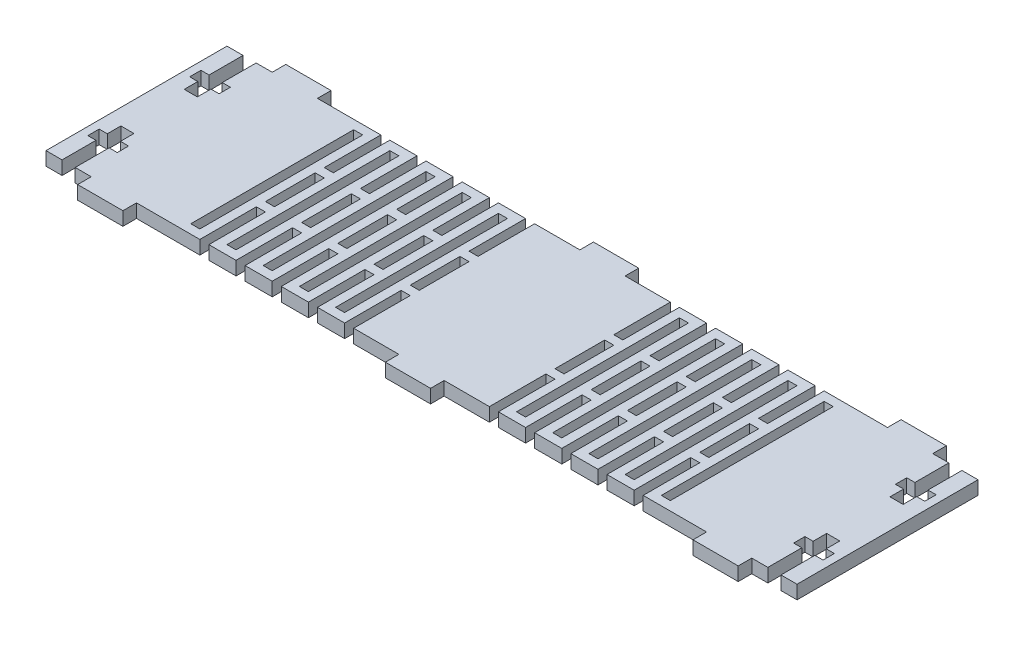
SolidWorks part; units mm, degrees
ref_plane "Front Plane" through (0, 0, 0) normal (0, 0, 1) x (1, 0, 0)
ref_plane "Top Plane" through (0, 0, 0) normal (0, 1, 0) x (1, 0, 0)
ref_plane "Right Plane" through (0, 0, 0) normal (1, 0, 0) x (0, 0, -1)
sketch "Sketch1" plane through (0, 0, 0) normal (0, 1, 0) x (1, 0, 0)
  line L0 (-53, 38) -> (-53, 2)
  line L1 (-83, 40) -> (-79.45, 40)
  line L2 (-83, 40) -> (-83, 0)
  line L3 (-83, 0) -> (-79.45, 0)
  line L5 (-15, 40) -> (-15, 27.5)
  line L8 (-51, 38) -> (-51, 2)
  line L9 (-49, 40) -> (-49, 27.5)
  line L10 (-47, 40) -> (-47, 27.5)
  line L11 (-45, 38) -> (-45, 2)
  line L12 (-43, 38) -> (-43, 2)
  line L13 (-41, 40) -> (-41, 27.5)
  line L14 (-39, 40) -> (-39, 27.5)
  line L15 (-37, 38) -> (-37, 2)
  line L16 (-35, 38) -> (-35, 2)
  line L17 (-33, 40) -> (-33, 27.5)
  line L18 (-31, 40) -> (-31, 27.5)
  line L19 (-29, 38) -> (-29, 2)
  line L20 (-27, 38) -> (-27, 2)
  line L21 (-25, 40) -> (-25, 27.5)
  line L22 (-23, 40) -> (-23, 27.5)
  line L23 (-21, 38) -> (-21, 2)
  line L24 (-19, 38) -> (-19, 2)
  line L25 (-17, 40) -> (-17, 27.5)
  line L44 (-53, 38) -> (-51, 38)
  line L45 (-53, 2) -> (-51, 2)
  line L46 (-49, 27.5) -> (-47, 27.5)
  line L47 (-49, 25.5) -> (-47, 25.5)
  line L48 (-49, 14.5) -> (-47, 14.5)
  line L49 (-49, 12.5) -> (-47, 12.5)
  line L50 (-45, 38) -> (-43, 38)
  line L51 (-47, 0) -> (-41, 0)
  line L52 (-49, 25.5) -> (-49, 14.5)
  line L53 (-49, 12.5) -> (-49, 0)
  line L54 (-45, 2) -> (-43, 2)
  line L55 (-39, 0) -> (-33, 0)
  line L56 (-41, 12.5) -> (-39, 12.5)
  line L57 (-41, 14.5) -> (-39, 14.5)
  line L58 (-41, 25.5) -> (-39, 25.5)
  line L59 (-41, 27.5) -> (-39, 27.5)
  line L60 (-47, 12.5) -> (-47, 0)
  line L61 (-47, 25.5) -> (-47, 14.5)
  line L62 (-47, 40) -> (-41, 40)
  line L63 (-33, 12.5) -> (-33, 0)
  line L64 (-41, 25.5) -> (-41, 14.5)
  line L65 (-39, 25.5) -> (-39, 14.5)
  line L66 (-41, 12.5) -> (-41, 0)
  line L67 (-39, 12.5) -> (-39, 0)
  line L68 (-39, 40) -> (-33, 40)
  line L69 (-31, 12.5) -> (-31, 0)
  line L70 (-33, 25.5) -> (-33, 14.5)
  line L71 (-31, 25.5) -> (-31, 14.5)
  line L72 (-37, 38) -> (-35, 38)
  line L73 (-37, 2) -> (-35, 2)
  line L74 (-29, 2) -> (-27, 2)
  line L75 (-33, 12.5) -> (-31, 12.5)
  line L76 (-33, 14.5) -> (-31, 14.5)
  line L77 (-33, 25.5) -> (-31, 25.5)
  line L78 (-33, 27.5) -> (-31, 27.5)
  line L79 (-29, 38) -> (-27, 38)
  line L80 (-23, 40) -> (-17, 40)
  line L81 (-25, 27.5) -> (-23, 27.5)
  line L82 (-23, 0) -> (-17, 0)
  line L83 (-25, 14.5) -> (-23, 14.5)
  line L84 (-25, 12.5) -> (-23, 12.5)
  line L85 (-31, 0) -> (-25, 0)
  line L86 (-31, 40) -> (-25, 40)
  line L87 (-25, 25.5) -> (-23, 25.5)
  line L88 (-25, 25.5) -> (-25, 14.5)
  line L89 (-23, 25.5) -> (-23, 14.5)
  line L90 (-17, 12.5) -> (-17, 0)
  line L91 (-21, 38) -> (-19, 38)
  line L93 (-17, 27.5) -> (-15, 27.5)
  line L94 (-17, 25.5) -> (-15, 25.5)
  line L95 (-15, 12.5) -> (-15, 0)
  line L96 (-17, 25.5) -> (-17, 14.5)
  line L97 (-15, 25.5) -> (-15, 14.5)
  line L98 (-25, 12.5) -> (-25, 0)
  line L99 (-23, 12.5) -> (-23, 0)
  line L100 (-21, 2) -> (-19, 2)
  line L102 (-17, 12.5) -> (-15, 12.5)
  line L103 (-17, 14.5) -> (-15, 14.5)
  line L110 (-15, 0) -> (-5, 0)
  line L116 (-15, 40) -> (-5, 40)
  line L125 (0, 40) -> (0, 0) construction
  line L128 (-73, 0) -> (-73, -3)
  line L129 (-73, -3) -> (-63, -3)
  line L130 (-63, 0) -> (-63, -3)
  line L131 (-63, 0) -> (-49, 0)
  line L134 (-5, 0) -> (-5, -3)
  line L135 (-5, -3) -> (5, -3)
  line L139 (-73, 40) -> (-73, 43)
  line L140 (-73, 43) -> (-63, 43)
  line L141 (-63, 40) -> (-63, 43)
  line L144 (-5, 40) -> (-5, 43)
  line L145 (-5, 43) -> (5, 43)
  line L147 (-63, 40) -> (-49, 40)
  line L148 (63, 40) -> (49, 40)
  line L150 (5, 40) -> (5, 43)
  line L151 (63, 40) -> (63, 43)
  line L152 (73, 43) -> (63, 43)
  line L153 (73, 40) -> (73, 43)
  line L155 (5, 0) -> (5, -3)
  line L156 (63, 0) -> (49, 0)
  line L157 (63, 0) -> (63, -3)
  line L158 (73, -3) -> (63, -3)
  line L159 (73, 0) -> (73, -3)
  line L160 (15, 40) -> (5, 40)
  line L161 (15, 0) -> (5, 0)
  line L162 (17, 14.5) -> (15, 14.5)
  line L163 (17, 12.5) -> (15, 12.5)
  line L164 (21, 2) -> (19, 2)
  line L165 (23, 12.5) -> (23, 0)
  line L166 (25, 12.5) -> (25, 0)
  line L167 (15, 25.5) -> (15, 14.5)
  line L168 (17, 25.5) -> (17, 14.5)
  line L169 (15, 12.5) -> (15, 0)
  line L170 (17, 25.5) -> (15, 25.5)
  line L171 (17, 27.5) -> (15, 27.5)
  line L172 (21, 38) -> (19, 38)
  line L173 (17, 12.5) -> (17, 0)
  line L174 (23, 25.5) -> (23, 14.5)
  line L175 (25, 25.5) -> (25, 14.5)
  line L176 (25, 25.5) -> (23, 25.5)
  line L177 (31, 40) -> (25, 40)
  line L178 (31, 0) -> (25, 0)
  line L179 (25, 12.5) -> (23, 12.5)
  line L180 (25, 14.5) -> (23, 14.5)
  line L181 (23, 0) -> (17, 0)
  line L182 (25, 27.5) -> (23, 27.5)
  line L183 (23, 40) -> (17, 40)
  line L184 (29, 38) -> (27, 38)
  line L185 (33, 27.5) -> (31, 27.5)
  line L186 (33, 25.5) -> (31, 25.5)
  line L187 (33, 14.5) -> (31, 14.5)
  line L188 (33, 12.5) -> (31, 12.5)
  line L189 (29, 2) -> (27, 2)
  line L190 (37, 2) -> (35, 2)
  line L191 (37, 38) -> (35, 38)
  line L192 (31, 25.5) -> (31, 14.5)
  line L193 (33, 25.5) -> (33, 14.5)
  line L194 (31, 12.5) -> (31, 0)
  line L195 (39, 40) -> (33, 40)
  line L196 (39, 12.5) -> (39, 0)
  line L197 (41, 12.5) -> (41, 0)
  line L198 (39, 25.5) -> (39, 14.5)
  line L199 (41, 25.5) -> (41, 14.5)
  line L200 (33, 12.5) -> (33, 0)
  line L201 (47, 40) -> (41, 40)
  line L202 (47, 25.5) -> (47, 14.5)
  line L203 (47, 12.5) -> (47, 0)
  line L204 (41, 27.5) -> (39, 27.5)
  line L205 (41, 25.5) -> (39, 25.5)
  line L206 (41, 14.5) -> (39, 14.5)
  line L207 (41, 12.5) -> (39, 12.5)
  line L208 (39, 0) -> (33, 0)
  line L209 (45, 2) -> (43, 2)
  line L210 (49, 12.5) -> (49, 0)
  line L211 (49, 25.5) -> (49, 14.5)
  line L212 (47, 0) -> (41, 0)
  line L213 (45, 38) -> (43, 38)
  line L214 (49, 12.5) -> (47, 12.5)
  line L215 (49, 14.5) -> (47, 14.5)
  line L216 (49, 25.5) -> (47, 25.5)
  line L217 (49, 27.5) -> (47, 27.5)
  line L218 (53, 2) -> (51, 2)
  line L219 (53, 38) -> (51, 38)
  line L220 (17, 40) -> (17, 27.5)
  line L221 (19, 38) -> (19, 2)
  line L222 (21, 38) -> (21, 2)
  line L223 (23, 40) -> (23, 27.5)
  line L224 (25, 40) -> (25, 27.5)
  line L225 (27, 38) -> (27, 2)
  line L226 (29, 38) -> (29, 2)
  line L227 (31, 40) -> (31, 27.5)
  line L228 (33, 40) -> (33, 27.5)
  line L229 (35, 38) -> (35, 2)
  line L230 (37, 38) -> (37, 2)
  line L231 (39, 40) -> (39, 27.5)
  line L232 (41, 40) -> (41, 27.5)
  line L233 (43, 38) -> (43, 2)
  line L234 (45, 38) -> (45, 2)
  line L235 (47, 40) -> (47, 27.5)
  line L236 (49, 40) -> (49, 27.5)
  line L237 (51, 38) -> (51, 2)
  line L238 (15, 40) -> (15, 27.5)
  line L239 (83, 0) -> (79.45, 0)
  line L240 (83, 40) -> (83, 0)
  line L241 (83, 40) -> (79.45, 40)
  line L242 (53, 38) -> (53, 2)
  line L243 (-76.55, 10) -> (-74.75, 10)
  line L245 (-79.45, 0) -> (-79.45, 7.5)
  line L246 (-79.45, 13) -> (-76.55, 13)
  line L247 (-76.55, 0) -> (-76.55, 7.5)
  line L248 (-81.25, 10) -> (-79.45, 10)
  line L249 (-81.25, 10) -> (-81.25, 7.5)
  line L250 (-81.25, 7.5) -> (-79.45, 7.5)
  line L251 (-74.75, 10) -> (-74.75, 7.5)
  line L252 (-79.45, 10) -> (-79.45, 13)
  line L253 (-76.55, 7.5) -> (-74.75, 7.5)
  line L254 (-76.55, 10) -> (-76.55, 13)
  line L255 (-76.55, 32.5) -> (-74.75, 32.5)
  line L256 (-79.45, 27) -> (-76.55, 27)
  line L257 (-79.45, 27) -> (-79.45, 30)
  line L259 (-76.55, 27) -> (-76.55, 30)
  line L260 (-81.25, 32.5) -> (-79.45, 32.5)
  line L261 (-81.25, 32.5) -> (-81.25, 30)
  line L262 (-81.25, 30) -> (-79.45, 30)
  line L263 (-74.75, 32.5) -> (-74.75, 30)
  line L264 (-79.45, 32.5) -> (-79.45, 40)
  line L265 (-76.55, 30) -> (-74.75, 30)
  line L266 (-76.55, 32.5) -> (-76.55, 40)
  line L267 (81.25, 10) -> (81.25, 7.5)
  line L268 (81.25, 7.5) -> (79.45, 7.5)
  line L269 (79.45, 0) -> (79.45, 7.5)
  line L271 (76.55, 0) -> (76.55, 7.5)
  line L272 (76.55, 7.5) -> (74.75, 7.5)
  line L273 (74.75, 10) -> (74.75, 7.5)
  line L274 (76.55, 10) -> (74.75, 10)
  line L275 (76.55, 10) -> (76.55, 13)
  line L276 (79.45, 13) -> (76.55, 13)
  line L277 (79.45, 10) -> (79.45, 13)
  line L278 (81.25, 10) -> (79.45, 10)
  line L279 (76.55, 32.5) -> (76.55, 40)
  line L281 (79.45, 32.5) -> (79.45, 40)
  line L282 (81.25, 32.5) -> (79.45, 32.5)
  line L283 (81.25, 32.5) -> (81.25, 30)
  line L284 (81.25, 30) -> (79.45, 30)
  line L285 (79.45, 27) -> (79.45, 30)
  line L286 (79.45, 27) -> (76.55, 27)
  line L287 (76.55, 27) -> (76.55, 30)
  line L288 (76.55, 30) -> (74.75, 30)
  line L289 (74.75, 32.5) -> (74.75, 30)
  line L290 (76.55, 32.5) -> (74.75, 32.5)
  line L291 (-76.55, 40) -> (-73, 40)
  line L292 (-76.55, 0) -> (-73, 0)
  line L293 (76.55, 0) -> (73, 0)
  line L294 (76.55, 40) -> (73, 40)
  point P12 (-68, -3)
  point P56 (-68, 43)
  point P60 (0, 43)
  point P65 (0, -3)
  point P203 (-78, 13)
  point P221 (-78, 27)
  dimension "D2" = 40
  dimension "D3" = 30
  dimension "D4" = 38
  dimension "D5" = 15
  dimension "D6" = 10
  dimension "D7" = 19
  dimension "D9" = 2
  dimension "D10" = 2
  dimension "D11" = 2
  dimension "D12" = 2
  dimension "D13" = 12.5
  dimension "D14" = 12.5
  dimension "D15" = 15
  dimension "D8" = 3
  dimension "D16" = 3
  dimension "D17" = 5
  dimension "D18" = 10
  dimension "D19" = 3
  dimension "D20" = 15
  dimension "D21" = 3
  dimension "D22" = 5
  dimension "D23" = 2.5
  dimension "D24" = 6.5
  dimension "D25" = 2.9
  dimension "D26" = 13
  dimension "D27" = 3
  dimension "D28" = 5
  dimension "D29" = 5
  dimension "D30" = 2.9
  dimension "D31" = 3
  dimension "D32" = 2.5
  dimension "D33" = 6.5
  dimension "D34" = 13
extrude "Boss-Extrude1" add sketch "Sketch1" along normal blind 3
